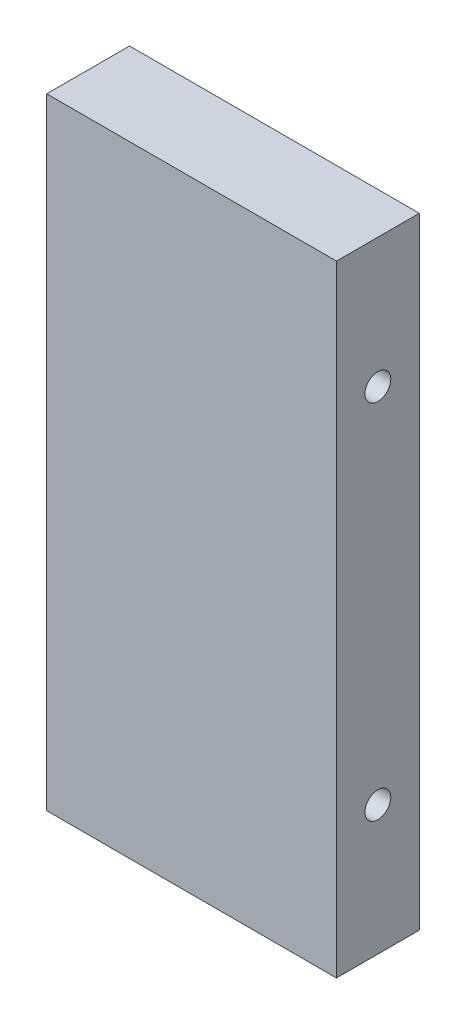
SolidWorks part; units mm, degrees
material "2024-T3"
ref_plane "正面" through (0, 0, 0) normal (0, 0, 1) x (1, 0, 0)
ref_plane "平面" through (0, 0, 0) normal (0, 1, 0) x (1, 0, 0)
ref_plane "右側面" through (0, 0, 0) normal (1, 0, 0) x (0, 0, -1)
sketch "ｽｹｯﾁ1" plane through (0, 0, 0) normal (0, 0, 1) x (1, 0, 0)
  line L1 (0, 0) -> (28, 0)
  line L2 (0, 0) -> (0, 60)
  line L3 (0, 60) -> (28, 60)
  line L4 (28, 0) -> (28, 60)
  dimension "D1" = 60
  dimension "D2" = 28
extrude "ﾎﾞｽ - 押し出し1" add sketch "ｽｹｯﾁ1" along normal blind 8
hole_wizard "M3x0.5 ねじ穴1" positions "3Dｽｹｯﾁ1" profile "ｽｹｯﾁ2" tap size "M3x0.5" standard "JIS"
sketch3d "3Dｽｹｯﾁ1"
  line L0 (0, 60, 8) -> (0, 60, 0) construction
  line L1 (0, 60, 0) -> (0, 0, 0) construction
  line L2 (0, 0, 8) -> (0, 0, 0) construction
  point P0 (0, 47.5, 4)
  point P2 (0, 12.5, 4)
  dimension "D1" = 12.5
  dimension "D2" = 4
  dimension "D3" = 4
  dimension "D4" = 12.5
sketch "ｽｹｯﾁ2" plane through (0, 47.5, 4) normal (0, 1, 0) x (0, 0, 1)
  line L0 (0, 0) -> (0, 8.2511)
  line L1 (0, 8.2511) -> (1.25, 7.5)
  line L2 (1.25, 7.5) -> (1.25, 0)
  line L5 (1.25, 0) -> (0, 0)
  line L10 (0, 8.2511) -> (-1.25, 7.5) construction
  line L11 (0, -6.35) -> (0, 107.95) construction
  dimension "ねじ下穴ﾄﾞﾘﾙ直径" = 2.5
  dimension "ねじ下穴ﾄﾞﾘﾙの深さ" = 7.5
  dimension "ﾄﾞﾘﾙ角度" = 118
cosmetic thread "穴のねじ山1"
cosmetic thread "穴のねじ山2"
hole_wizard "M3x0.5 ねじ穴2" positions "3Dｽｹｯﾁ2" profile "ｽｹｯﾁ3" tap size "M3x0.5" standard "JIS"
sketch3d "3Dｽｹｯﾁ2"
  line L0 (28, 60, 8) -> (28, 60, 0) construction
  line L1 (28, 0, 8) -> (28, 60, 8) construction
  line L2 (28, 0, 8) -> (28, 0, 0) construction
  point P0 (28, 47.5, 4)
  point P2 (28, 12.5, 4)
  dimension "D1" = 12.5
  dimension "D2" = 4
  dimension "D3" = 12.5
  dimension "D4" = 4
sketch "ｽｹｯﾁ3" plane through (28, 47.5, 4) normal (0, 1, 0) x (0, 0, -1)
  line L0 (0, 0) -> (0, 8.2511)
  line L1 (0, 8.2511) -> (1.25, 7.5)
  line L2 (1.25, 7.5) -> (1.25, 0)
  line L5 (1.25, 0) -> (0, 0)
  line L10 (0, 8.2511) -> (-1.25, 7.5) construction
  line L11 (0, -6.35) -> (0, 107.95) construction
  dimension "ねじ下穴ﾄﾞﾘﾙ直径" = 2.5
  dimension "ねじ下穴ﾄﾞﾘﾙの深さ" = 7.5
  dimension "ﾄﾞﾘﾙ角度" = 118
cosmetic thread "穴のねじ山3"
cosmetic thread "穴のねじ山4"
